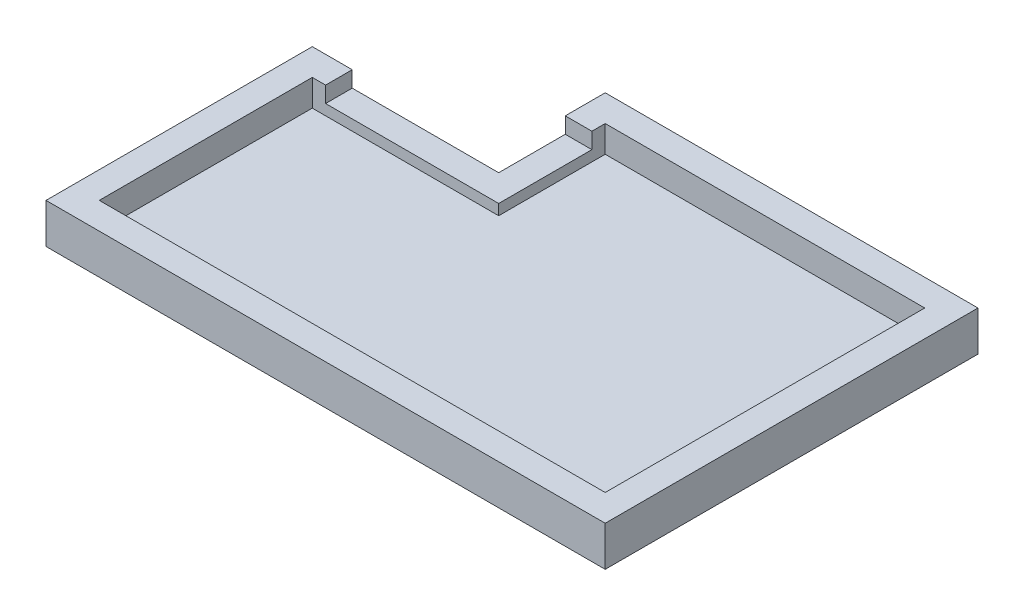
SolidWorks part; units mm, degrees
ref_plane "Front Plane" through (0, 0, 0) normal (0, 0, 1) x (1, 0, 0)
ref_plane "Top Plane" through (0, 0, 0) normal (0, 1, 0) x (1, 0, 0)
ref_plane "Right Plane" through (0, 0, 0) normal (1, 0, 0) x (0, 0, -1)
sketch "Sketch1" plane through (0, 0, 0) normal (0, 1, 0) x (1, 0, 0)
  line L0 (0, 0) -> (0, 127)
  line L3 (0, 127) -> (88.9, 127)
  line L4 (88.9, 127) -> (88.9, 177.8)
  line L5 (88.9, 177.8) -> (266.7, 177.8)
  line L6 (266.7, 177.8) -> (266.7, 0)
  line L7 (266.7, 0) -> (0, 0)
  dimension "D2" = 266.7
  dimension "D3" = 177.8
  dimension "D4" = 88.9
  dimension "D6" = 50.8
  dimension "D7" = 177.8
extrude "Boss-Extrude1" add sketch "Sketch1" along normal blind 19.05
sketch "Sketch2" plane through (0, 19.05, 0) normal (0, 1, 0) x (1, 0, 0)
  line L0 (12.7, 114.3) -> (101.6, 114.3)
  line L1 (101.6, 114.3) -> (101.6, 165.1)
  line L2 (101.6, 165.1) -> (254, 165.1)
  line L3 (254, 165.1) -> (254, 12.7)
  line L4 (254, 12.7) -> (12.7, 12.7)
  line L5 (12.7, 12.7) -> (12.7, 114.3)
  line L7 (0, 0) -> (266.7, 0) construction
  line L8 (266.7, 0) -> (266.7, 177.8) construction
  line L9 (266.7, 177.8) -> (88.9, 177.8) construction
  line L10 (88.9, 177.8) -> (88.9, 127) construction
  line L11 (88.9, 127) -> (0, 127) construction
  line L12 (0, 127) -> (0, 0) construction
  dimension "D1" = 12.7
  dimension "D2" = 12.7
  dimension "D3" = 12.7
  dimension "D4" = 12.7
  dimension "D5" = 12.7
  dimension "D6" = 12.7
extrude "Cut-Extrude1" cut sketch "Sketch2" against normal blind 12.7
sketch "Sketch3" plane through (0, 19.05, 0) normal (0, 1, 0) x (1, 0, 0)
  line L0 (19.05, 127) -> (19.05, 114.3)
  line L1 (88.9, 127) -> (0, 127) construction
  line L2 (101.6, 114.3) -> (12.7, 114.3) construction
  line L3 (19.05, 114.3) -> (101.6, 114.3)
  line L4 (101.6, 114.3) -> (101.6, 158.75)
  line L5 (101.6, 165.1) -> (101.6, 114.3) construction
  line L6 (101.6, 158.75) -> (88.9, 158.75)
  line L7 (88.9, 177.8) -> (88.9, 127) construction
  line L8 (88.9, 158.75) -> (88.9, 127)
  line L9 (88.9, 127) -> (19.05, 127)
  line L10 (12.7, 114.3) -> (12.7, 12.7) construction
  line L11 (254, 165.1) -> (101.6, 165.1) construction
  dimension "D1" = 6.35
  dimension "D2" = 6.35
extrude "Cut-Extrude2" cut sketch "Sketch3" against normal blind 7.62
